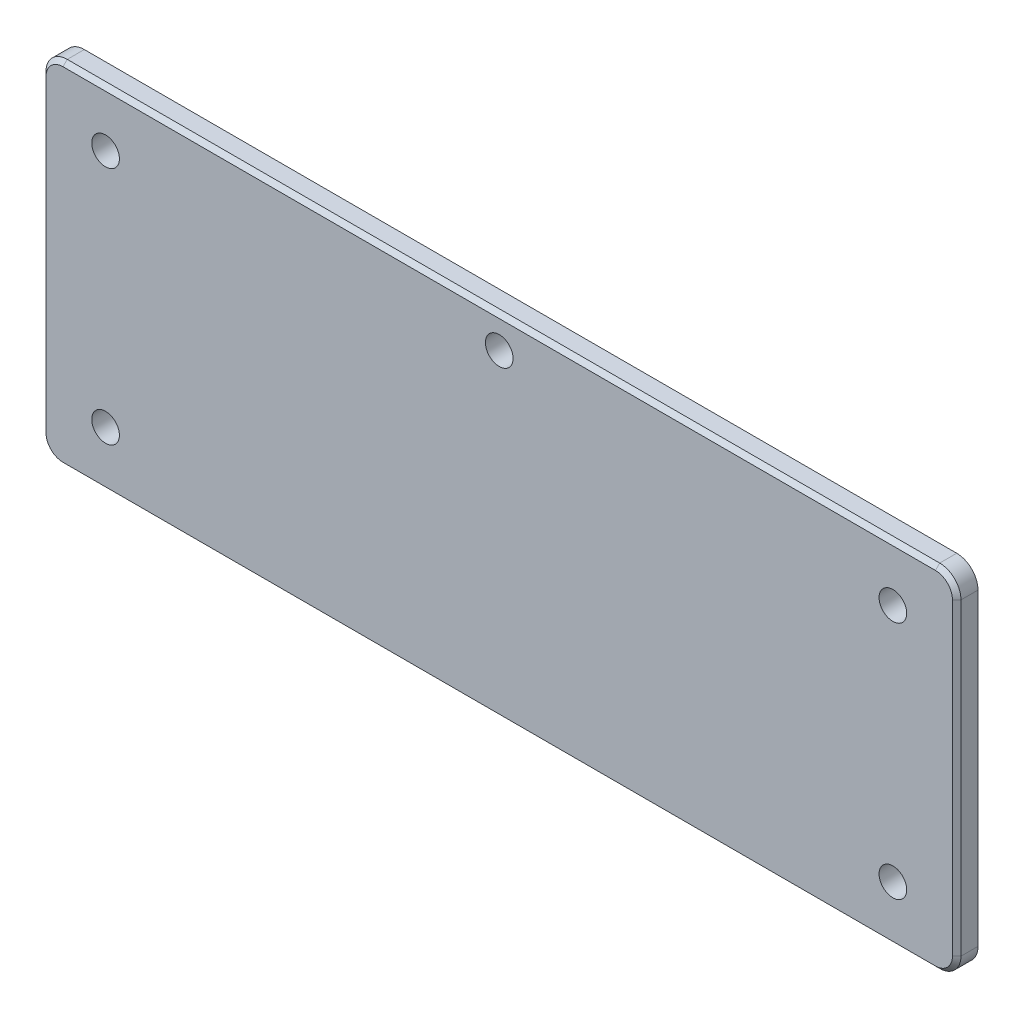
SolidWorks part; units mm, degrees
ref_plane "Plane XZ" through (0, 0, 0) normal (0, 0, 1) x (1, 0, 0)
ref_plane "Plane XY" through (0, 0, 0) normal (0, 1, 0) x (1, 0, 0)
ref_plane "Plane YZ" through (0, 0, 0) normal (1, 0, 0) x (0, 0, -1)
sketch "Sketch1" plane through (0, 0, 0) normal (0, 0, 1) x (1, 0, 0)
  line L0 (-55.88, -14.2875) -> (55.88, -14.2875) construction
  line L1 (-55.88, 22.225) -> (55.88, 22.225) construction
  line L2 (-55.88, 22.225) -> (-55.88, -22.225) construction
  line L3 (-55.88, -22.225) -> (55.88, -22.225) construction
  line L4 (55.88, 22.225) -> (55.88, -22.225) construction
  line L5 (0, 0) -> (0, -14.2875) construction
  line L6 (0, 0) -> (-55.88, 0) construction
  line L7 (-54.61, 20.955) -> (54.61, 20.955)
  line L8 (54.61, 20.955) -> (54.61, -20.955)
  line L9 (-54.61, -20.955) -> (54.61, -20.955)
  line L10 (-54.61, 20.955) -> (-54.61, -20.955)
  dimension "D1" = 111.76
  dimension "D2" = 44.45
  dimension "D3" = 14.2875
  dimension "D4" = 1.27
extrude "Boss-Extrude1" add sketch "Sketch1" along normal blind 2.54
sketch "Sketch4" plane through (0, 0, 2.54) normal (0, 0, 1) x (1, 0, 0)
  line L0 (-46.99, 0) -> (46.99, 0) construction
  line L1 (-46.99, 14.2875) -> (46.99, 14.2875) construction
  line L2 (-46.99, 14.2875) -> (-46.99, -14.2875) construction
  line L3 (-46.99, -14.2875) -> (46.99, -14.2875) construction
  line L4 (46.99, 14.2875) -> (46.99, -14.2875) construction
  circle A0 centre (-46.99, 14.2875) radius 1.651
  circle A1 centre (-46.99, -14.2875) radius 1.651
  circle A2 centre (46.99, -14.2875) radius 1.651
  circle A3 centre (46.99, 14.2875) radius 1.651
  dimension "D1" = 3.302
  dimension "D4" = 3.302
  dimension "D2" = 93.98
  dimension "D3" = 28.575
extrude "Cut-Extrude2" cut sketch "Sketch4" against normal through all and the other way through all
fillet "Fillet1" radius 2.54 4 edges at (54.61, 20.955, 1.27) (54.61, -20.955, 1.27) (-54.61, -20.955, 1.27) (-54.61, 20.955, 1.27)
sketch "Sketch14" plane through (0, 0, 2.54) normal (0, 0, 1) x (1, 0, 0)
  circle A0 centre (0, 17.145) radius 1.651
  dimension "D2" = 3.302
  dimension "D1" = 17.145
extrude "Cut-Extrude8" cut sketch "Sketch14" against normal through all
chamfer "Chamfer2" distance 0.508 angle 45 8 edges at (54.61, 0, 2.54) (53.8661, 20.2111, 2.54) (53.8661, -20.2111, 2.54) (0, 20.955, 2.54) (0, -20.955, 2.54) (-53.8661, 20.2111, 2.54) (-53.8661, -20.2111, 2.54) (-54.61, 0, 2.54)
